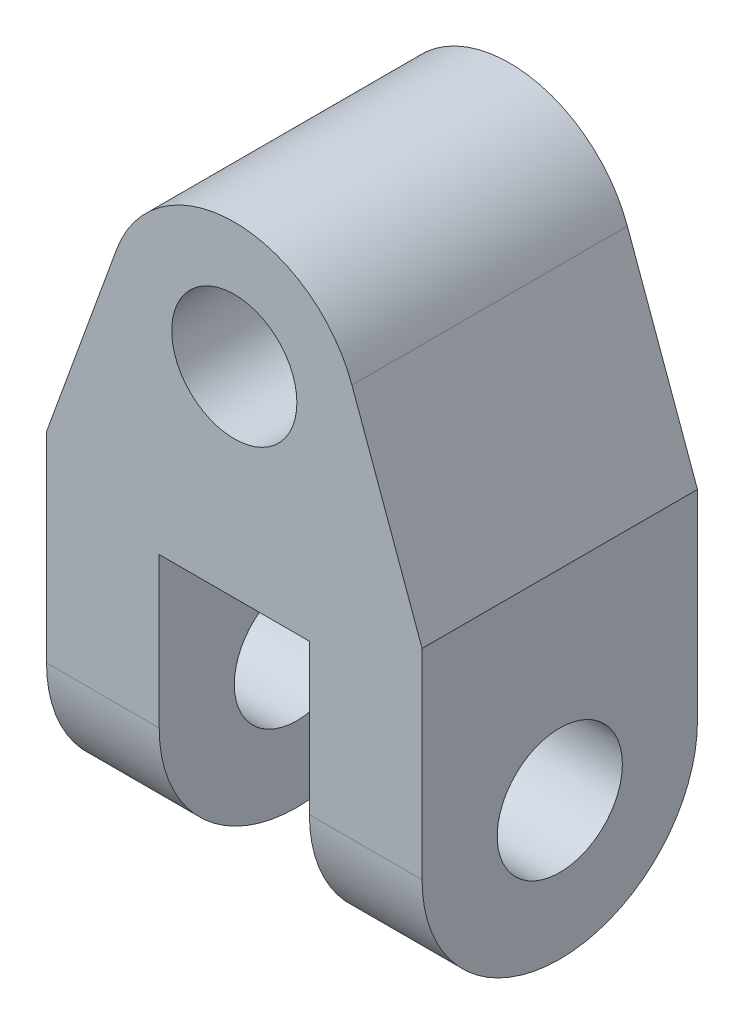
SolidWorks part; units mm, degrees
ref_plane "Front Plane" through (0, 0, 0) normal (0, 0, 1) x (1, 0, 0)
ref_plane "Top Plane" through (0, 0, 0) normal (0, 1, 0) x (1, 0, 0)
ref_plane "Right Plane" through (0, 0, 0) normal (1, 0, 0) x (0, 0, -1)
sketch "Sketch1" plane through (0, 0, 0) normal (0, 0, 1) x (1, 0, 0)
  line L0 (0, 94854.0167) -> (0, -101467.3854) construction
  line L1 (-131320.7902, 0) -> (105891.0954, 0) construction
  line L2 (-30000, -24000) -> (-30000, -78000)
  line L3 (-30000, -78000) -> (-12000, -78000)
  line L4 (-12000, -78000) -> (-12000, -32000)
  line L5 (-12000, -32000) -> (12000, -32000)
  line L6 (12000, -32000) -> (12000, -78000)
  line L7 (12000, -78000) -> (30000, -78000)
  line L8 (30000, -78000) -> (30000, -24000)
  line L9 (-18797.5411, 6830.2597) -> (-30000, -24000)
  line L10 (18797.5411, 6830.2597) -> (30000, -24000)
  circle A0 centre (0, 0) radius 10000
  arc A1 (18797.5411, 6830.2597) -> (-18797.5411, 6830.2597) centre (0, 0) ccw
  dimension "D1" = 40000
  dimension "D2" = 20000
  dimension "D3" = 12000
  dimension "D4" = 24000
  dimension "D5" = 18000
  dimension "D6" = 18000
  dimension "D7" = 46000
  dimension "D8" = 46000
  dimension "D9" = 78000
  dimension "D10" = 54000
  dimension "D11" = 54000
extrude "Boss-Extrude3" add sketch "Sketch1" along normal blind 44000
sketch "Sketch2" plane through (30000, 0, 0) normal (1, 0, 0) x (0, 0, -1)
  line L0 (0, -78000) -> (0, -24000) construction
  circle A0 centre (-22000, -56000) radius 10000
  dimension "D1" = 20000
  dimension "D2" = 22000
  dimension "D3" = 22000
extrude "Cut-Extrude1" cut sketch "Sketch2" against normal through all
sketch "Sketch3" plane through (30000, 0, 0) normal (1, 0, 0) x (0, 0, -1)
  line L0 (0, -78000) -> (0, -24000) construction
  line L1 (-44000, -78000) -> (0, -78000) construction
  line L2 (-44000, -78000) -> (-44000, -24000) construction
  line L3 (0, -78000) -> (0, -56000)
  line L4 (-44000, -78000) -> (0, -78000)
  line L5 (-44000, -78000) -> (-44000, -56000)
  arc A0 (-44000, -56000) -> (0, -56000) centre (-22000, -56000) ccw
  line M3 (0, -78000) -> (0, -24000)
  line M5 (-44000, -24000) -> (-44000, -78000)
  line M6 (-44000, -78000) -> (0, -78000)
  dimension "D1" = 44000
  dimension "D2" = 22000
  dimension "D3" = 22000
extrude "Cut-Extrude2" cut sketch "Sketch3" against normal through all contours A0 M5 M6 | A0 L4 M3
